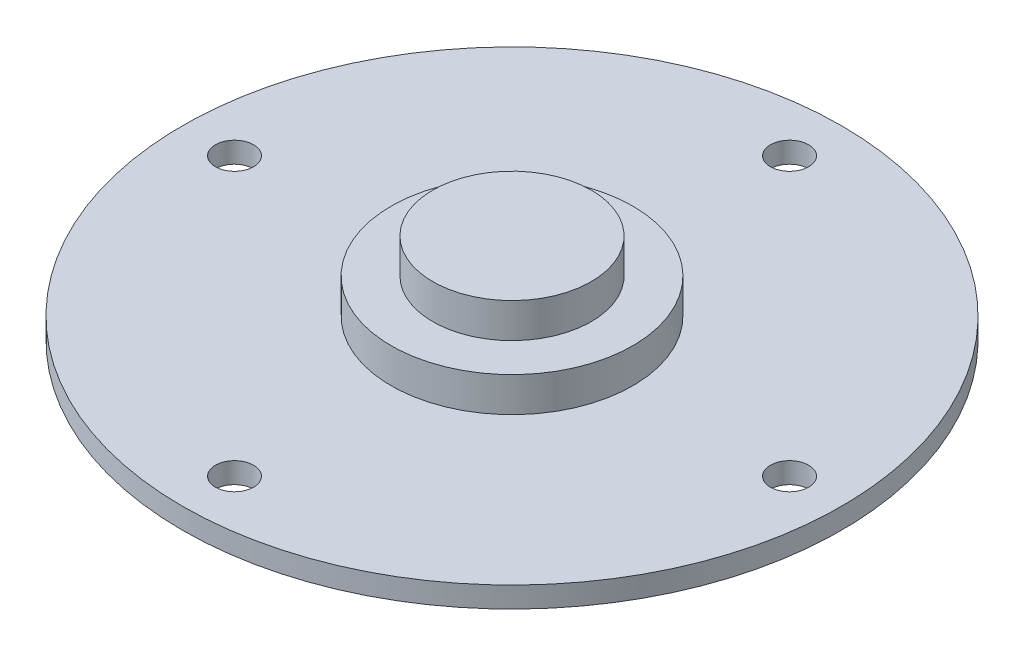
SolidWorks part; units mm, degrees
ref_plane "Front Plane" through (0, 0, 0) normal (0, 0, 1) x (1, 0, 0)
ref_plane "Top Plane" through (0, 0, 0) normal (0, 1, 0) x (1, 0, 0)
ref_plane "Right Plane" through (0, 0, 0) normal (1, 0, 0) x (0, 0, -1)
sketch "Sketch5" plane through (0, 0, 0) normal (1, 0, 0) x (0, 0, -1)
  line L0 (34.85, 6) -> (95, 6)
  line L1 (0, 0) -> (95, 0)
  line L2 (0, 0) -> (0, 26)
  line L4 (95, 0) -> (95, 6)
  line L5 (0, 26) -> (22.85, 26)
  line L8 (22.85, 26) -> (22.85, 16)
  line L9 (0, 0) -> (0, 65.0916) construction
  line L10 (22.85, 16) -> (34.85, 16)
  line L11 (34.85, 16) -> (34.85, 6)
  dimension "D1" = 45.7
  dimension "D2" = 190
  dimension "D3" = 20
  dimension "D4" = 6
  dimension "D5" = 10
  dimension "D6" = 12
revolve "Revolve1" add sketch "Sketch5" angle 360 about L9
hole_wizard "M10 Clearance Hole1" positions "3DSketch1" profile "Sketch7" hole size "M10" standard "ANSI Metric" end condition through all
sketch3d "3DSketch1"
  line L2 (0, 6, -80) -> (0, 6, 0) construction
  line L3 (0, 26, 0) -> (0, 16, 0) construction
  point P0 (0, 6, -80)
  dimension "D1" = 80
sketch "Sketch7" plane through (0, 6, -80) normal (1, 0, 0) x (0, 0, 1)
  line L0 (0, 0) -> (0, 6)
  line L1 (0, 6) -> (5.5, 6)
  line L2 (5.5, 6) -> (5.5, 0)
  line L5 (5.5, 0) -> (0, 0)
  line L11 (0, -6.35) -> (0, 107.95) construction
  dimension "Thru Hole Dia." = 11
  dimension "Thru Hole Depth" = 6
pattern_circular "CirPattern1" count 4 over 360 about axis through (0, 0, 0) along (0, 1, 0) of "M10 Clearance Hole1"
